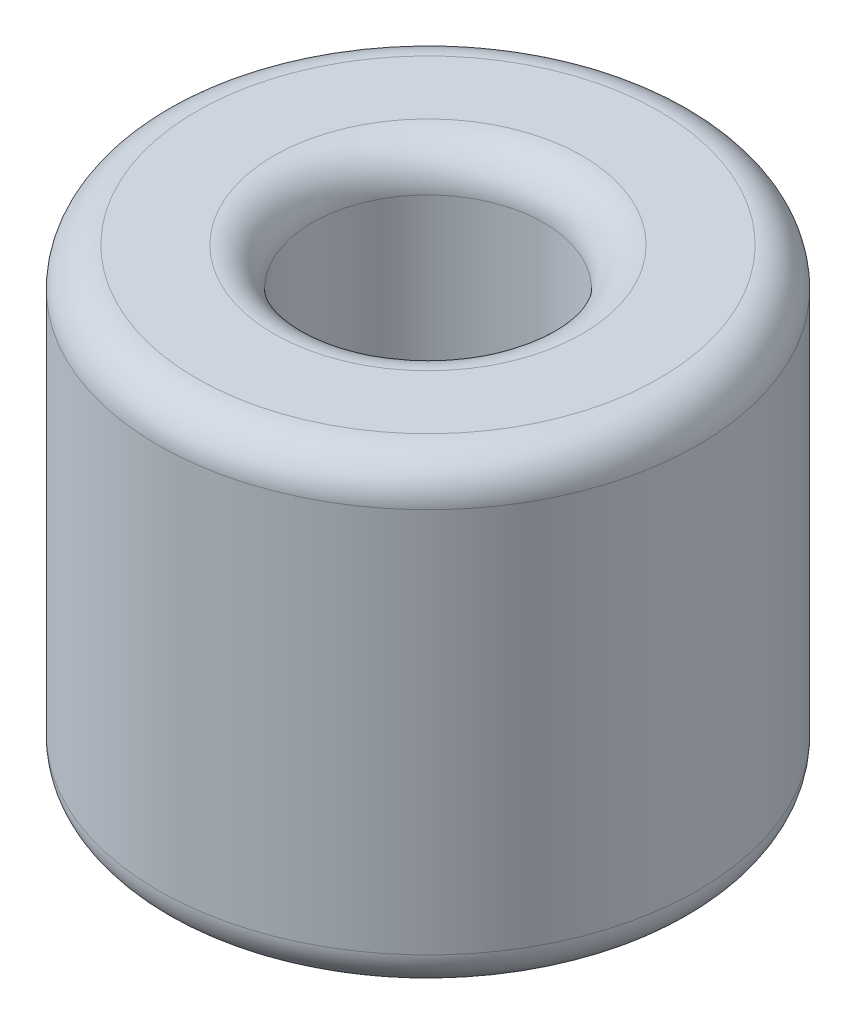
SolidWorks part; units mm, degrees
ref_plane "Front" through (0, 0, 0) normal (0, 0, 1) x (1, 0, 0)
ref_plane "Top" through (0, 0, 0) normal (0, 1, 0) x (1, 0, 0)
ref_plane "Right" through (0, 0, 0) normal (1, 0, 0) x (0, 0, -1)
sketch "Sketch1" plane through (0, 0, 0) normal (0, 1, 0) x (1, 0, 0)
  circle A0 centre (0, 0) radius 1.5
  circle A1 centre (0, 0) radius 3.5
  dimension "D1" = 3
  dimension "D2" = 7
extrude "Boss-Extrude1" add sketch "Sketch1" along normal blind 6
fillet "Fillet1" radius 0.5 4 edges at (0, 0, 1.5) (0, 0, 3.5) (0, 6, 1.5) (0, 6, 3.5)
